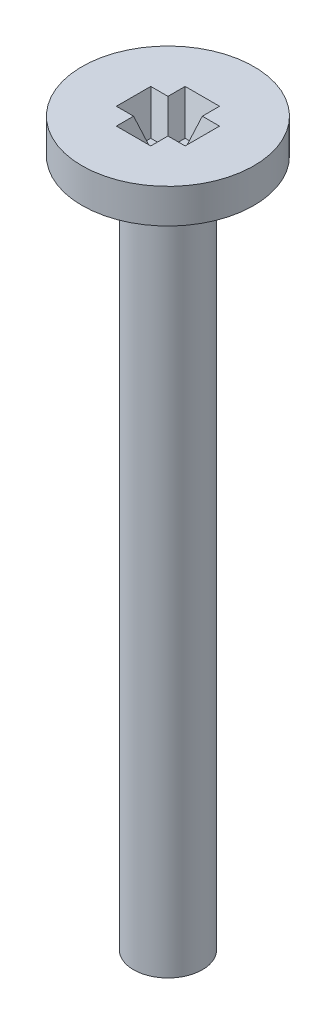
SolidWorks part; units mm, degrees
ref_plane "Front Plane" through (0, 0, 0) normal (0, 0, 1) x (1, 0, 0)
ref_plane "Top Plane" through (0, 0, 0) normal (0, 1, 0) x (1, 0, 0)
ref_plane "Right Plane" through (0, 0, 0) normal (1, 0, 0) x (0, 0, -1)
sketch "Sketch1" plane through (0, 0, 0) normal (0, 1, 0) x (1, 0, 0)
  circle A0 centre (0, 0) radius 5
extrude "Boss-Extrude1" add sketch "Sketch1" along normal blind 2
sketch "Sketch2" plane through (0, 2, 0) normal (0, 1, 0) x (1, 0, 0)
  line L0 (0, -2) -> (0, 2)
  line L1 (0, 0) -> (2.6543, 0) construction
  line L2 (-2, 0) -> (2, 0)
  dimension "D1" = 2
  dimension "D2" = 2
  dimension "D3" = 2
  dimension "D4" = 2
extrude "Cut-Extrude-Thin1" cut sketch "Sketch2" against normal blind 2 draft 17 thin thin type two direction wall 1 second wall 1
sketch "Sketch3" plane through (0, 0, 0) normal (0, -1, 0) x (1, 0, 0)
  circle A0 centre (0, 0) radius 2
extrude "Boss-Extrude2" add sketch "Sketch3" along normal blind 40
